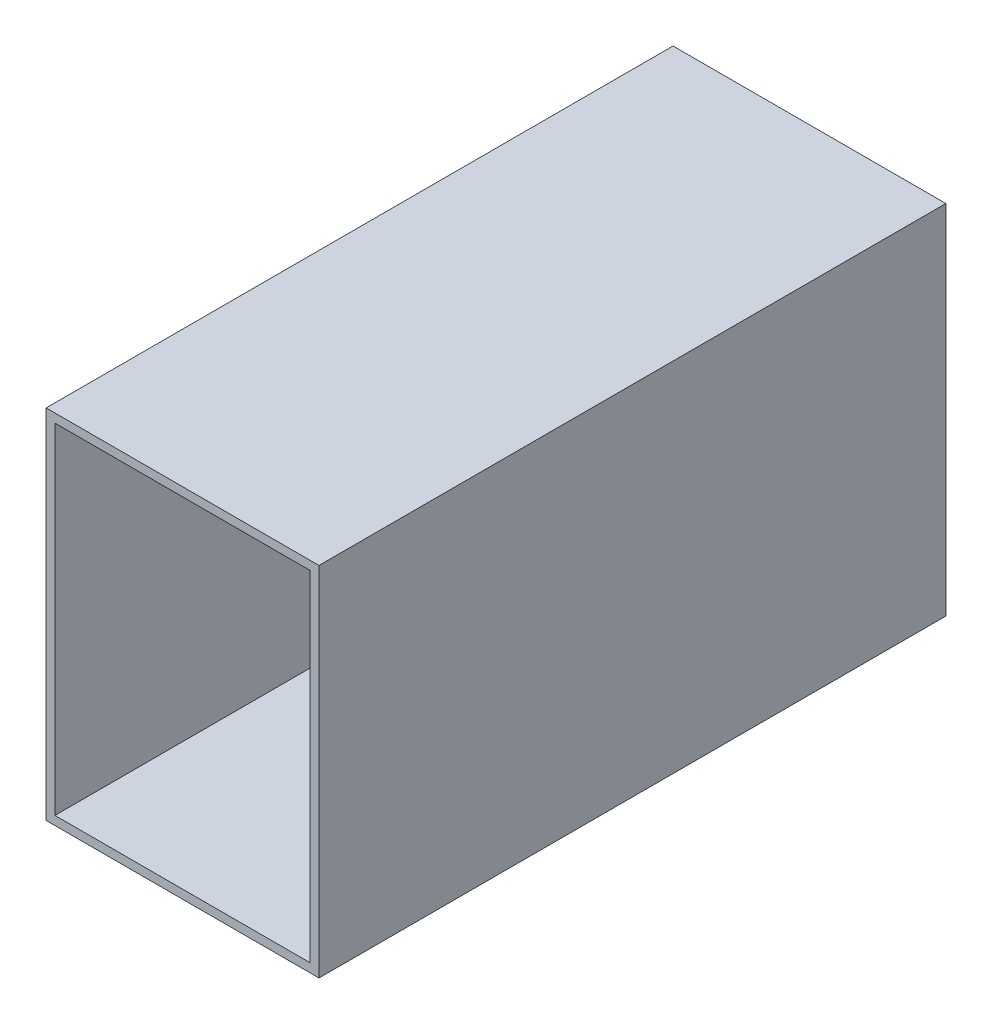
SolidWorks part; units mm, degrees
ref_plane "Plan de face" through (0, 0, 0) normal (0, 0, 1) x (1, 0, 0)
ref_plane "Plan de dessus" through (0, 0, 0) normal (0, 1, 0) x (1, 0, 0)
ref_plane "Plan de droite" through (0, 0, 0) normal (1, 0, 0) x (0, 0, -1)
sketch "Esquisse1" plane through (0, 0, 0) normal (0, 0, 1) x (1, 0, 0)
  line L1 (0, 0) -> (840, 0)
  line L2 (0, 0) -> (0, 1100)
  line L3 (0, 1100) -> (840, 1100)
  line L4 (840, 0) -> (840, 1100)
  dimension "D1" = 840
  dimension "D2" = 1100
extrude "Boss.-Extru.1" add sketch "Esquisse1" along normal blind 30
sketch "Esquisse2" plane through (0, 0, 30) normal (0, 0, 1) x (1, 0, 0)
  line L0 (27, 1073) -> (27, 27)
  line L1 (27, 27) -> (813, 27)
  line L2 (813, 27) -> (813, 1073)
  line L3 (813, 1073) -> (27, 1073)
  line L4 (0, 1100) -> (0, 0)
  line L5 (0, 0) -> (840, 0)
  line L6 (840, 0) -> (840, 1100)
  line L7 (840, 1100) -> (0, 1100)
  line L8 (0, 1100) -> (0, 0)
  line L9 (0, 0) -> (840, 0)
  line L10 (840, 0) -> (840, 1100)
  line L11 (840, 1100) -> (0, 1100)
  dimension "D1" = 0
  dimension "D2" = 27
extrude "Boss.-Extru.2" add sketch "Esquisse2" along normal blind 1900
sketch "Esquisse4" plane through (0, 1100, 0) normal (0, 1, 0) x (1, 0, 0)
  line L0 (27, -1930) -> (27, -30) construction
  line L1 (27, -457) -> (813, -457)
  line L2 (27, -457) -> (27, -430)
  line L3 (27, -430) -> (813, -430)
  line L4 (813, -457) -> (813, -430)
  line L5 (813, -1930) -> (813, -30) construction
  line L6 (813, -30) -> (27, -30) construction
  dimension "D1" = 27
  dimension "D2" = 400
extrude "Boss.-Extru.3" add sketch "Esquisse4" against normal blind 540
